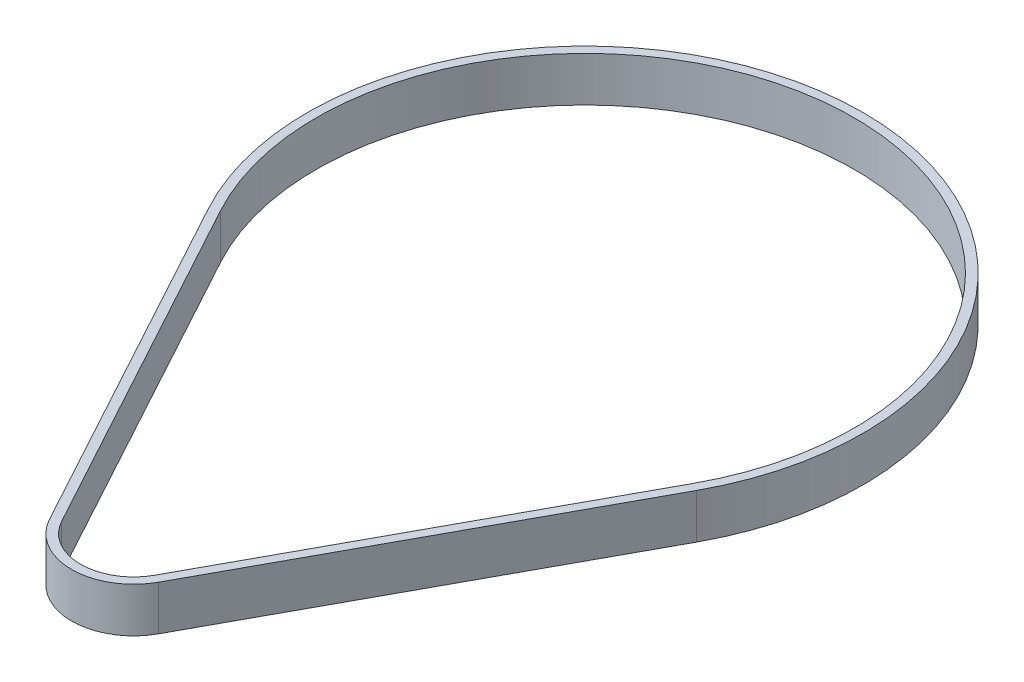
SolidWorks part; units mm, degrees
ref_plane "前视基准面" through (0, 0, 0) normal (0, 0, 1) x (1, 0, 0)
ref_plane "上视基准面" through (0, 0, 0) normal (0, 1, 0) x (1, 0, 0)
ref_plane "右视基准面" through (0, 0, 0) normal (1, 0, 0) x (0, 0, -1)
sketch "草图1" plane through (0, 0, 0) normal (0, 1, 0) x (1, 0, 0)
  line L0 (12.1791, -6.6262) -> (54.558, 71.267)
  line L1 (-12.1791, -6.6262) -> (-54.558, 71.267)
  line L2 (0, 0) -> (0, 100.95)
  line L3 (-10.4223, -5.6704) -> (-52.8012, 72.2228)
  line L4 (10.4223, -5.6704) -> (52.8012, 72.2228)
  arc A0 (-10.4223, -5.6704) -> (10.4223, -5.6704) centre (0, 0) ccw
  arc A1 (52.8012, 72.2228) -> (-52.8012, 72.2228) centre (0, 100.95) ccw
  arc A2 (-12.1791, -6.6262) -> (12.1791, -6.6262) centre (0, 0) ccw
  arc A3 (54.558, 71.267) -> (-54.558, 71.267) centre (0, 100.95) ccw
  dimension "D1" = 100.95
  dimension "D2" = 23.73
  dimension "D3" = 120.22
  dimension "D4" = 2
extrude "凸台-拉伸1" add sketch "草图1" along normal blind 10 contours L0 A3 L1 A2 A1 L4 A0 L3
